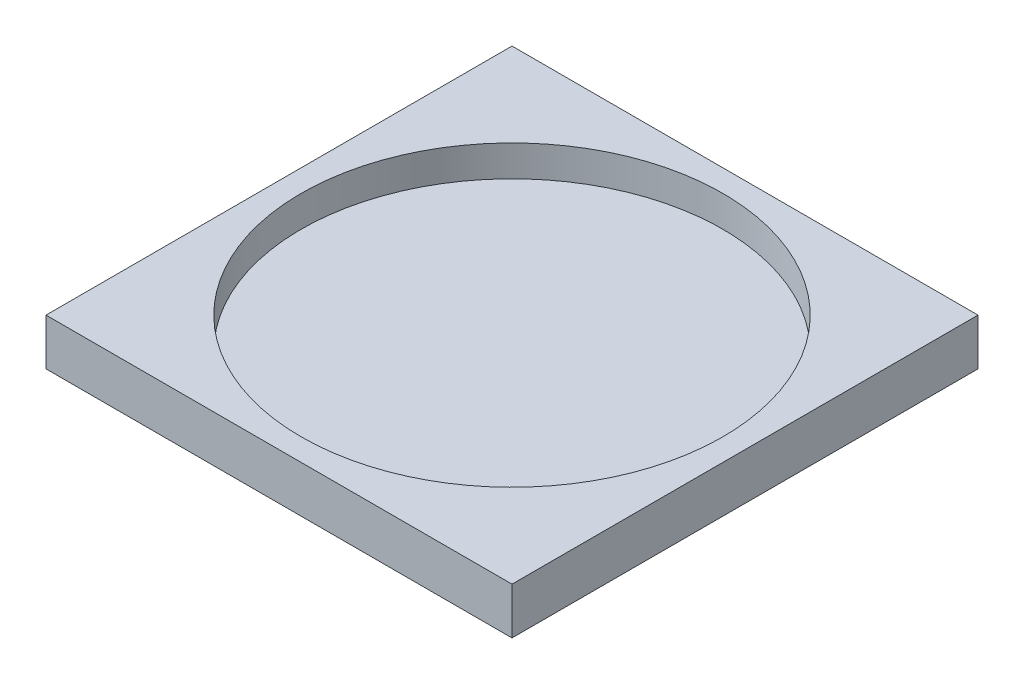
SolidWorks part; units mm, degrees
ref_plane "Alzado" through (0, 0, 0) normal (0, 0, 1) x (1, 0, 0)
ref_plane "Planta" through (0, 0, 0) normal (0, 1, 0) x (1, 0, 0)
ref_plane "Vista lateral" through (0, 0, 0) normal (1, 0, 0) x (0, 0, -1)
sketch "Croquis1" plane through (0, 0, 0) normal (0, 1, 0) x (1, 0, 0)
  line L1 (-15, -15) -> (15, -15)
  line L2 (-15, -15) -> (-15, 15)
  line L3 (-15, 15) -> (15, 15)
  line L4 (15, -15) -> (15, 15)
  line L5 (-15, -15) -> (15, 15) construction
  line L6 (-15, 15) -> (15, -15) construction
  point P0 (0, 0)
  dimension "D1" = 30
  dimension "D2" = 30
extrude "Saliente-Extruir1" add sketch "Croquis1" along normal blind 3
sketch "Croquis2" plane through (0, 3, 0) normal (0, 1, 0) x (1, 0, 0)
  circle A0 centre (0, 0) radius 13.575
  dimension "D1" = 27.15
extrude "Cortar-Extruir1" cut sketch "Croquis2" against normal blind 2
